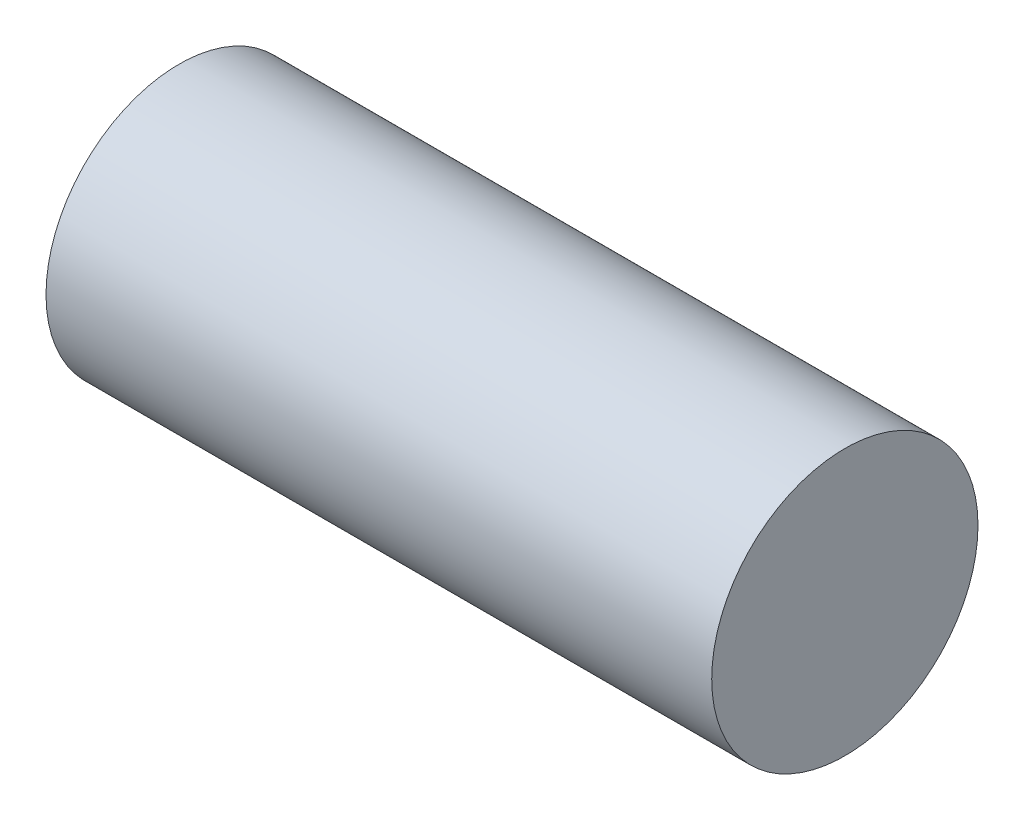
SolidWorks part; units mm, degrees
ref_plane "Front Plane" through (0, 0, 0) normal (0, 0, 1) x (1, 0, 0)
ref_plane "Top Plane" through (0, 0, 0) normal (0, 1, 0) x (1, 0, 0)
ref_plane "Right Plane" through (0, 0, 0) normal (1, 0, 0) x (0, 0, -1)
sketch "Sketch1" plane through (0, 0, 0) normal (1, 0, 0) x (0, 0, -1)
  circle A0 centre (0, 0) radius 2.5
  dimension "D1" = 5
extrude "Boss-Extrude1" add sketch "Sketch1" along normal blind 12.5
